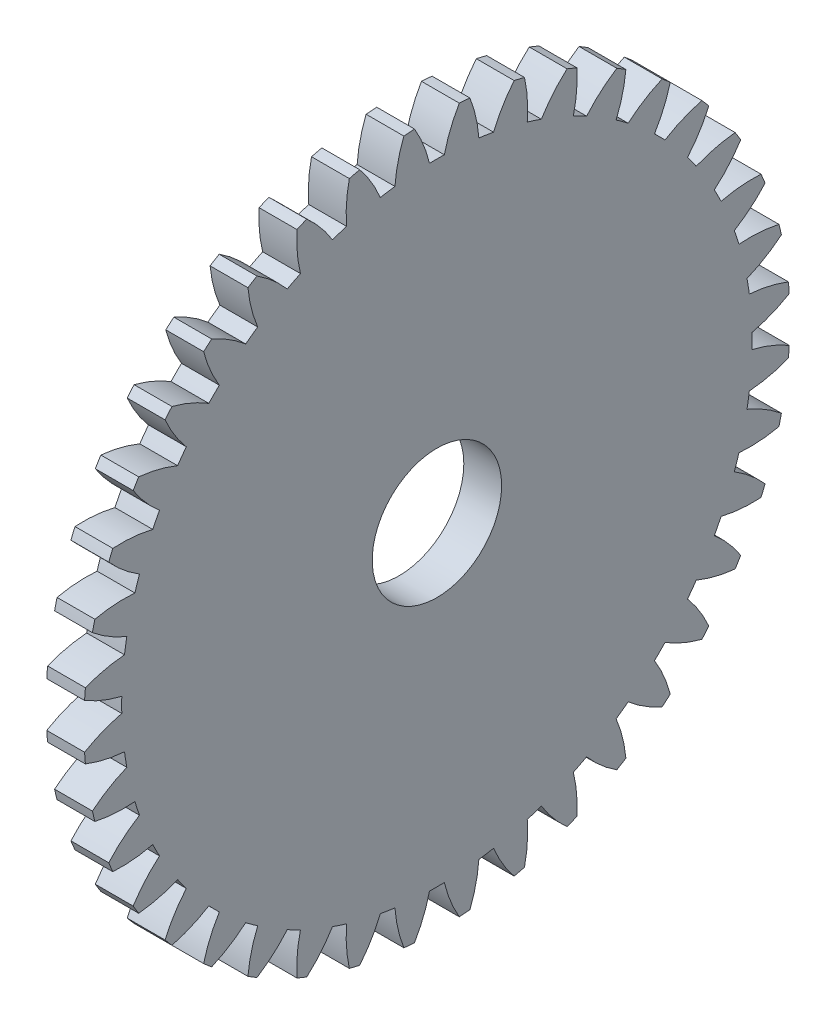
SolidWorks part; units mm, degrees
ref_plane "Plane1" through (0, 0, 0) normal (0, 0, 1) x (1, 0, 0)
ref_plane "Plane2" through (0, 0, 0) normal (0, 1, 0) x (1, 0, 0)
ref_plane "Plane3" through (0, 0, 0) normal (1, 0, 0) x (0, 0, -1)
other "Configuration Table"
sketch "HoldingSke" plane through (0, 0, 0) normal (0, 1, 0) x (1, 0, 0)
  line L0 (0, 0) -> (0.383, -0.3214)
  line L1 (-15, 0) -> (100, 0) construction
  line L2 (0, 0) -> (-2.1039, 2.3779)
  line L3 (0, 0) -> (-11.863, 4.5341)
  line L4 (0, 0) -> (6.6156, 5.5511)
  line L5 (0, 0) -> (-46.8476, -17.4728)
  line L6 (0, 0) -> (-3.7303, -2.5169)
  line L7 (-2.1039, 2.3779) -> (8.6586, 51.2059)
  line L8 (-76.2, 54.61) -> (-74.4, 54.61)
  line L9 (-71.009, 38.7566) -> (-53.1078, 45.2721)
  line L10 (-76.2, 71.12) -> (104.1128, 71.12)
  line L11 (0, 0) -> (-4.5, 0)
  line L12 (-76.2, 101.6) -> (-76.133, 101.6)
  line L13 (24.9733, 27.94) -> (52.9518, 28.4284)
  line L14 (24.9733, 27.94) -> (24.9743, 27.94)
  line L15 (24.9733, 27.94) -> (100.4006, 29.5858)
  line L16 (-63.627, -2) -> (-12.827, -2)
  circle A0 centre (0, 0) radius 5
  circle A1 centre (0, 0) radius 37.499
  circle A2 centre (0, 0) radius 37.5
  circle A3 centre (0, 0) radius 5
  dimension "MHD" = 74.998
  dimension "Hub_dia" = 75
  dimension "Bore" = 10
  dimension "MBD" = 10
  dimension "Num_teeth" = 40
  dimension "Pitch" = 0.5
  dimension "Overall_len" = 50
  dimension "Show_teeth" = 40
  dimension "Thickness" = 4.5
  dimension "OAL" = 50.0001
  dimension "T_dim" = 1.8
  dimension "Ap" = 20
  dimension "H" = 19.05
  dimension "Pitch_radius" = 180.3128
  dimension "Width" = 4.5
  dimension "Backlash" = 0.067
  dimension "Addendum_fac" = 1
  dimension "Dedendum_fac" = 1.25
  dimension "Clearance_fac" = 0.25
  dimension "Dedendum_add" = 0.001
  dimension "Module" = 2
sketch "BasProSke" plane through (0, 0, 0) normal (0, 1, 0) x (1, 0, 0)
  line L0 (-10, 0) -> (60, 0) construction
  line L1 (0, 0) -> (0, 42)
  line L2 (0, 0) -> (4.5, 0)
  line L3 (4.5, 0) -> (4.5, 42)
  line L4 (4.5, 42) -> (0, 42)
  dimension "Thickness" = 4.5
  dimension "Diameter" = 84
revolve "Base-Revolve" add sketch "BasProSke" angle 360 about L0
sketch "TooCutSke" plane through (0, 0, 0) normal (1, 0, 0) x (0, 0, -1)
  line L1 (0, 0) -> (0, 107) construction
  line L2 (0, 0) -> (-1.6876, 39.9644) construction
  line L3 (0, 0) -> (-6.2726, 79.7007) construction
  line L4 (-1.6876, 39.9644) -> (-3.1363, 39.8504) construction
  arc A0 (0.8828, 37.4886) -> (-0.8828, 37.4886) centre (0, 0) ccw
  arc A1 (2.6784, 41.94) -> (-2.6784, 41.94) centre (0, 0) ccw
  circle A2 centre (0, 0) radius 40 construction
  circle A3 centre (0, 0) radius 37.5877 construction
  arc A4 (-0.8828, 37.4886) -> (-2.6784, 41.94) centre (-16.451, 33.7965) ccw
  arc A5 (2.6784, 41.94) -> (0.8828, 37.4886) centre (16.451, 33.7965) ccw
  dimension "Root_dia" = 74.998
  dimension "Overcut_dia" = 84.0508
  dimension "Pitch_dia" = 80
  dimension "Base_dia" = 75.1754
  dimension "Flank_rad" = 16
  dimension "Half_ang" = 4.5
  dimension "Half_CT" = 1.4531
extrude "ToothCut" cut sketch "TooCutSke" along normal through all
fillet "Breaks" [suppressed] radius 0.04
fillet "RootFillets" [suppressed] radius 0.501
pattern_circular "TeethCuts" count 40 every 9 about axis through (-10, 0, 0) along (1, 0, 0) of "ToothCut", "RootFillets", "Breaks"
sketch "HubNeaOneSke" plane through (0, 0, 0) normal (-1, 0, 0) x (0, 0, 1)
  circle A0 centre (0, 0) radius 37.499
  dimension "Diameter" = 74.998
extrude "HubNearOne" [suppressed] add sketch "HubNeaOneSke" along normal blind 45.5001
sketch "HubNeaBotSke" plane through (0, 0, 0) normal (-1, 0, 0) x (0, 0, 1)
  circle A0 centre (0, 0) radius 37.499
  dimension "Diameter" = 74.998
extrude "HubNearBoth" [suppressed] add sketch "HubNeaBotSke" along normal blind 22.75
ref_plane "FarPln" through (4.5, 0, 0) normal (1, 0, 0) x (0, 0, -1)
sketch "HubFarSke" plane through (4.5, 0, 0) normal (1, 0, 0) x (0, 0, -1)
  circle A0 centre (0, 0) radius 37.499
  dimension "Diameter" = 74.998
extrude "HubFar" [suppressed] add sketch "HubFarSke" along normal blind 22.75
sketch "BorSke" plane through (0, 0, 0) normal (1, 0, 0) x (0, 0, -1)
  circle A0 centre (0, 0) radius 5
  dimension "Diameter" = 10
extrude "Bore" cut sketch "BorSke" along normal mid plane 100.0001
sketch "KeySke" plane through (0, 0, 0) normal (1, 0, 0) x (0, 0, -1)
  line L0 (-2, 0) -> (-2, 6.8)
  line L1 (-2, 6.8) -> (2, 6.8)
  line L2 (2, 6.8) -> (2, 0)
  line L3 (0, 0) -> (0, 34) construction
  line L4 (-2, 0) -> (2, 0)
  dimension "Offset" = 6.8
  dimension "Width" = 4
extrude "Keyway" [suppressed] cut sketch "KeySke" along normal mid plane 100.0001
pattern_circular "Keyway2" [suppressed] count 2 every 90 about axis through (-10, 0, 0) along (1, 0, 0)
sketch "Sketch1" plane through (4.5, 0, 0) normal (1, 0, 0) x (0, 0, -1)
  circle A0 centre (0, 0) radius 7.7
  arc A160 (-41.9154, 2.664) -> (-37.4886, 0.8828) centre (-33.7965, 16.451) ccw
  arc A161 (-37.4886, 0.8828) -> (-37.4886, -0.8828) centre (0, 0) ccw
  arc A162 (-37.4886, -0.8828) -> (-41.9154, -2.664) centre (-33.7965, -16.451) ccw
  arc A163 (-41.9154, -2.664) -> (-41.8161, -3.9259) centre (0, 0) ccw
  arc A164 (-41.8161, -3.9259) -> (-37.1652, -4.9926) centre (-35.9539, 10.9615) ccw
  arc A165 (-37.1652, -4.9926) -> (-36.889, -6.7365) centre (0, 0) ccw
  arc A166 (-36.889, -6.7365) -> (-40.9826, -9.1882) centre (-30.8069, -21.5354) ccw
  arc A167 (-40.9826, -9.1882) -> (-40.6872, -10.419) centre (0, 0) ccw
  arc A168 (-40.6872, -10.419) -> (-35.9266, -10.745) centre (-37.226, 5.2021) ccw
  arc A169 (-35.9266, -10.745) -> (-35.381, -12.4242) centre (0, 0) ccw
  arc A170 (-35.381, -12.4242) -> (-39.0407, -15.4862) centre (-27.0587, -26.0895) ccw
  arc A171 (-39.0407, -15.4862) -> (-38.5563, -16.6556) centre (0, 0) ccw
  arc A172 (-38.5563, -16.6556) -> (-33.8034, -16.2329) centre (-37.5815, -0.6853) ccw
  arc A173 (-33.8034, -16.2329) -> (-33.0018, -17.8061) centre (0, 0) ccw
  arc A174 (-33.0018, -17.8061) -> (-36.1375, -21.4028) centre (-22.6443, -30.0012) ccw
  arc A175 (-36.1375, -21.4028) -> (-35.4761, -22.4821) centre (0, 0) ccw
  arc A176 (-35.4761, -22.4821) -> (-30.8478, -21.321) centre (-37.0116, -6.5559) ccw
  arc A177 (-30.8478, -21.321) -> (-29.81, -22.7495) centre (0, 0) ccw
  arc A178 (-29.81, -22.7495) -> (-32.3445, -26.7925) centre (-17.6723, -33.1742) ccw
  arc A179 (-32.3445, -26.7925) -> (-31.5224, -27.755) centre (0, 0) ccw
  arc A180 (-31.5224, -27.755) -> (-27.1327, -25.8842) centre (-35.5303, -12.2651) ccw
  arc A181 (-27.1327, -25.8842) -> (-25.8842, -27.1327) centre (0, 0) ccw
  arc A182 (-25.8842, -27.1327) -> (-27.755, -31.5224) centre (-12.2651, -35.5303) ccw
  arc A183 (-27.755, -31.5224) -> (-26.7925, -32.3445) centre (0, 0) ccw
  arc A184 (-26.7925, -32.3445) -> (-22.7495, -29.81) centre (-33.1742, -17.6723) ccw
  arc A185 (-22.7495, -29.81) -> (-21.321, -30.8478) centre (0, 0) ccw
  arc A186 (-21.321, -30.8478) -> (-22.4821, -35.4761) centre (-6.5559, -37.0116) ccw
  arc A187 (-22.4821, -35.4761) -> (-21.4028, -36.1375) centre (0, 0) ccw
  arc A188 (-21.4028, -36.1375) -> (-17.8061, -33.0018) centre (-30.0012, -22.6443) ccw
  arc A189 (-17.8061, -33.0018) -> (-16.2329, -33.8034) centre (0, 0) ccw
  arc A190 (-16.2329, -33.8034) -> (-16.6556, -38.5563) centre (-0.6853, -37.5815) ccw
  arc A191 (-16.6556, -38.5563) -> (-15.4862, -39.0407) centre (0, 0) ccw
  arc A192 (-15.4862, -39.0407) -> (-12.4242, -35.381) centre (-26.0895, -27.0587) ccw
  arc A193 (-12.4242, -35.381) -> (-10.745, -35.9266) centre (0, 0) ccw
  arc A194 (-10.745, -35.9266) -> (-10.419, -40.6872) centre (5.2021, -37.226) ccw
  arc A195 (-10.419, -40.6872) -> (-9.1882, -40.9826) centre (0, 0) ccw
  arc A196 (-9.1882, -40.9826) -> (-6.7365, -36.889) centre (-21.5354, -30.8069) ccw
  arc A197 (-6.7365, -36.889) -> (-4.9926, -37.1652) centre (0, 0) ccw
  arc A198 (-4.9926, -37.1652) -> (-3.9259, -41.8161) centre (10.9615, -35.9539) ccw
  arc A199 (-3.9259, -41.8161) -> (-2.664, -41.9154) centre (0, 0) ccw
  arc A200 (-2.664, -41.9154) -> (-0.8828, -37.4886) centre (-16.451, -33.7965) ccw
  arc A201 (-0.8828, -37.4886) -> (0.8828, -37.4886) centre (0, 0) ccw
  arc A202 (0.8828, -37.4886) -> (2.664, -41.9154) centre (16.451, -33.7965) ccw
  arc A203 (2.664, -41.9154) -> (3.9259, -41.8161) centre (0, 0) ccw
  arc A204 (3.9259, -41.8161) -> (4.9926, -37.1652) centre (-10.9615, -35.9539) ccw
  arc A205 (4.9926, -37.1652) -> (6.7365, -36.889) centre (0, 0) ccw
  arc A206 (6.7365, -36.889) -> (9.1882, -40.9826) centre (21.5354, -30.8069) ccw
  arc A207 (9.1882, -40.9826) -> (10.419, -40.6872) centre (0, 0) ccw
  arc A208 (10.419, -40.6872) -> (10.745, -35.9266) centre (-5.2021, -37.226) ccw
  arc A209 (10.745, -35.9266) -> (12.4242, -35.381) centre (0, 0) ccw
  arc A210 (12.4242, -35.381) -> (15.4862, -39.0407) centre (26.0895, -27.0587) ccw
  arc A211 (15.4862, -39.0407) -> (16.6556, -38.5563) centre (0, 0) ccw
  arc A212 (16.6556, -38.5563) -> (16.2329, -33.8034) centre (0.6853, -37.5815) ccw
  arc A213 (16.2329, -33.8034) -> (17.8061, -33.0018) centre (0, 0) ccw
  arc A214 (17.8061, -33.0018) -> (21.4028, -36.1375) centre (30.0012, -22.6443) ccw
  arc A215 (21.4028, -36.1375) -> (22.4821, -35.4761) centre (0, 0) ccw
  arc A216 (22.4821, -35.4761) -> (21.321, -30.8478) centre (6.5559, -37.0116) ccw
  arc A217 (21.321, -30.8478) -> (22.7495, -29.81) centre (0, 0) ccw
  arc A218 (22.7495, -29.81) -> (26.7925, -32.3445) centre (33.1742, -17.6723) ccw
  arc A219 (26.7925, -32.3445) -> (27.755, -31.5224) centre (0, 0) ccw
  arc A220 (27.755, -31.5224) -> (25.8842, -27.1327) centre (12.2651, -35.5303) ccw
  arc A221 (25.8842, -27.1327) -> (27.1327, -25.8842) centre (0, 0) ccw
  arc A222 (27.1327, -25.8842) -> (31.5224, -27.755) centre (35.5303, -12.2651) ccw
  arc A223 (31.5224, -27.755) -> (32.3445, -26.7925) centre (0, 0) ccw
  arc A224 (32.3445, -26.7925) -> (29.81, -22.7495) centre (17.6723, -33.1742) ccw
  arc A225 (29.81, -22.7495) -> (30.8478, -21.321) centre (0, 0) ccw
  arc A226 (30.8478, -21.321) -> (35.4761, -22.4821) centre (37.0116, -6.5559) ccw
  arc A227 (35.4761, -22.4821) -> (36.1375, -21.4028) centre (0, 0) ccw
  arc A228 (36.1375, -21.4028) -> (33.0018, -17.8061) centre (22.6443, -30.0012) ccw
  arc A229 (33.0018, -17.8061) -> (33.8034, -16.2329) centre (0, 0) ccw
  arc A230 (33.8034, -16.2329) -> (38.5563, -16.6556) centre (37.5815, -0.6853) ccw
  arc A231 (38.5563, -16.6556) -> (39.0407, -15.4862) centre (0, 0) ccw
  arc A232 (39.0407, -15.4862) -> (35.381, -12.4242) centre (27.0587, -26.0895) ccw
  arc A233 (35.381, -12.4242) -> (35.9266, -10.745) centre (0, 0) ccw
  arc A234 (35.9266, -10.745) -> (40.6872, -10.419) centre (37.226, 5.2021) ccw
  arc A235 (40.6872, -10.419) -> (40.9826, -9.1882) centre (0, 0) ccw
  arc A236 (40.9826, -9.1882) -> (36.889, -6.7365) centre (30.8069, -21.5354) ccw
  arc A237 (36.889, -6.7365) -> (37.1652, -4.9926) centre (0, 0) ccw
  arc A238 (37.1652, -4.9926) -> (41.8161, -3.9259) centre (35.9539, 10.9615) ccw
  arc A239 (41.8161, -3.9259) -> (41.9154, -2.664) centre (0, 0) ccw
  arc A240 (41.9154, -2.664) -> (37.4886, -0.8828) centre (33.7965, -16.451) ccw
  arc A241 (37.4886, -0.8828) -> (37.4886, 0.8828) centre (0, 0) ccw
  arc A242 (37.4886, 0.8828) -> (41.9154, 2.664) centre (33.7965, 16.451) ccw
  arc A243 (41.9154, 2.664) -> (41.8161, 3.9259) centre (0, 0) ccw
  arc A244 (41.8161, 3.9259) -> (37.1652, 4.9926) centre (35.9539, -10.9615) ccw
  arc A245 (37.1652, 4.9926) -> (36.889, 6.7365) centre (0, 0) ccw
  arc A246 (36.889, 6.7365) -> (40.9826, 9.1882) centre (30.8069, 21.5354) ccw
  arc A247 (40.9826, 9.1882) -> (40.6872, 10.419) centre (0, 0) ccw
  arc A248 (40.6872, 10.419) -> (35.9266, 10.745) centre (37.226, -5.2021) ccw
  arc A249 (35.9266, 10.745) -> (35.381, 12.4242) centre (0, 0) ccw
  arc A250 (35.381, 12.4242) -> (39.0407, 15.4862) centre (27.0587, 26.0895) ccw
  arc A251 (39.0407, 15.4862) -> (38.5563, 16.6556) centre (0, 0) ccw
  arc A252 (38.5563, 16.6556) -> (33.8034, 16.2329) centre (37.5815, 0.6853) ccw
  arc A253 (33.8034, 16.2329) -> (33.0018, 17.8061) centre (0, 0) ccw
  arc A254 (33.0018, 17.8061) -> (36.1375, 21.4028) centre (22.6443, 30.0012) ccw
  arc A255 (36.1375, 21.4028) -> (35.4761, 22.4821) centre (0, 0) ccw
  arc A256 (35.4761, 22.4821) -> (30.8478, 21.321) centre (37.0116, 6.5559) ccw
  arc A257 (30.8478, 21.321) -> (29.81, 22.7495) centre (0, 0) ccw
  arc A258 (29.81, 22.7495) -> (32.3445, 26.7925) centre (17.6723, 33.1742) ccw
  arc A259 (32.3445, 26.7925) -> (31.5224, 27.755) centre (0, 0) ccw
  arc A260 (31.5224, 27.755) -> (27.1327, 25.8842) centre (35.5303, 12.2651) ccw
  arc A261 (27.1327, 25.8842) -> (25.8842, 27.1327) centre (0, 0) ccw
  arc A262 (25.8842, 27.1327) -> (27.755, 31.5224) centre (12.2651, 35.5303) ccw
  arc A263 (27.755, 31.5224) -> (26.7925, 32.3445) centre (0, 0) ccw
  arc A264 (26.7925, 32.3445) -> (22.7495, 29.81) centre (33.1742, 17.6723) ccw
  arc A265 (22.7495, 29.81) -> (21.321, 30.8478) centre (0, 0) ccw
  arc A266 (21.321, 30.8478) -> (22.4821, 35.4761) centre (6.5559, 37.0116) ccw
  arc A267 (22.4821, 35.4761) -> (21.4028, 36.1375) centre (0, 0) ccw
  arc A268 (21.4028, 36.1375) -> (17.8061, 33.0018) centre (30.0012, 22.6443) ccw
  arc A269 (17.8061, 33.0018) -> (16.2329, 33.8034) centre (0, 0) ccw
  arc A270 (16.2329, 33.8034) -> (16.6556, 38.5563) centre (0.6853, 37.5815) ccw
  arc A271 (16.6556, 38.5563) -> (15.4862, 39.0407) centre (0, 0) ccw
  arc A272 (15.4862, 39.0407) -> (12.4242, 35.381) centre (26.0895, 27.0587) ccw
  arc A273 (12.4242, 35.381) -> (10.745, 35.9266) centre (0, 0) ccw
  arc A274 (10.745, 35.9266) -> (10.419, 40.6872) centre (-5.2021, 37.226) ccw
  arc A275 (10.419, 40.6872) -> (9.1882, 40.9826) centre (0, 0) ccw
  arc A276 (9.1882, 40.9826) -> (6.7365, 36.889) centre (21.5354, 30.8069) ccw
  arc A277 (6.7365, 36.889) -> (4.9926, 37.1652) centre (0, 0) ccw
  arc A278 (4.9926, 37.1652) -> (3.9259, 41.8161) centre (-10.9615, 35.9539) ccw
  arc A279 (3.9259, 41.8161) -> (2.664, 41.9154) centre (0, 0) ccw
  arc A280 (2.664, 41.9154) -> (0.8828, 37.4886) centre (16.451, 33.7965) ccw
  arc A281 (0.8828, 37.4886) -> (-0.8828, 37.4886) centre (0, 0) ccw
  arc A282 (-0.8828, 37.4886) -> (-2.664, 41.9154) centre (-16.451, 33.7965) ccw
  arc A283 (-2.664, 41.9154) -> (-3.9259, 41.8161) centre (0, 0) ccw
  arc A284 (-3.9259, 41.8161) -> (-4.9926, 37.1652) centre (10.9615, 35.9539) ccw
  arc A285 (-4.9926, 37.1652) -> (-6.7365, 36.889) centre (0, 0) ccw
  arc A286 (-6.7365, 36.889) -> (-9.1882, 40.9826) centre (-21.5354, 30.8069) ccw
  arc A287 (-9.1882, 40.9826) -> (-10.419, 40.6872) centre (0, 0) ccw
  arc A288 (-10.419, 40.6872) -> (-10.745, 35.9266) centre (5.2021, 37.226) ccw
  arc A289 (-10.745, 35.9266) -> (-12.4242, 35.381) centre (0, 0) ccw
  arc A290 (-12.4242, 35.381) -> (-15.4862, 39.0407) centre (-26.0895, 27.0587) ccw
  arc A291 (-15.4862, 39.0407) -> (-16.6556, 38.5563) centre (0, 0) ccw
  arc A292 (-16.6556, 38.5563) -> (-16.2329, 33.8034) centre (-0.6853, 37.5815) ccw
  arc A293 (-16.2329, 33.8034) -> (-17.8061, 33.0018) centre (0, 0) ccw
  arc A294 (-17.8061, 33.0018) -> (-21.4028, 36.1375) centre (-30.0012, 22.6443) ccw
  arc A295 (-21.4028, 36.1375) -> (-22.4821, 35.4761) centre (0, 0) ccw
  arc A296 (-22.4821, 35.4761) -> (-21.321, 30.8478) centre (-6.5559, 37.0116) ccw
  arc A297 (-21.321, 30.8478) -> (-22.7495, 29.81) centre (0, 0) ccw
  arc A298 (-22.7495, 29.81) -> (-26.7925, 32.3445) centre (-33.1742, 17.6723) ccw
  arc A299 (-26.7925, 32.3445) -> (-27.755, 31.5224) centre (0, 0) ccw
  arc A300 (-27.755, 31.5224) -> (-25.8842, 27.1327) centre (-12.2651, 35.5303) ccw
  arc A301 (-25.8842, 27.1327) -> (-27.1327, 25.8842) centre (0, 0) ccw
  arc A302 (-27.1327, 25.8842) -> (-31.5224, 27.755) centre (-35.5303, 12.2651) ccw
  arc A303 (-31.5224, 27.755) -> (-32.3445, 26.7925) centre (0, 0) ccw
  arc A304 (-32.3445, 26.7925) -> (-29.81, 22.7495) centre (-17.6723, 33.1742) ccw
  arc A305 (-29.81, 22.7495) -> (-30.8478, 21.321) centre (0, 0) ccw
  arc A306 (-30.8478, 21.321) -> (-35.4761, 22.4821) centre (-37.0116, 6.5559) ccw
  arc A307 (-35.4761, 22.4821) -> (-36.1375, 21.4028) centre (0, 0) ccw
  arc A308 (-36.1375, 21.4028) -> (-33.0018, 17.8061) centre (-22.6443, 30.0012) ccw
  arc A309 (-33.0018, 17.8061) -> (-33.8034, 16.2329) centre (0, 0) ccw
  arc A310 (-33.8034, 16.2329) -> (-38.5563, 16.6556) centre (-37.5815, 0.6853) ccw
  arc A311 (-38.5563, 16.6556) -> (-39.0407, 15.4862) centre (0, 0) ccw
  arc A312 (-39.0407, 15.4862) -> (-35.381, 12.4242) centre (-27.0587, 26.0895) ccw
  arc A313 (-35.381, 12.4242) -> (-35.9266, 10.745) centre (0, 0) ccw
  arc A314 (-35.9266, 10.745) -> (-40.6872, 10.419) centre (-37.226, -5.2021) ccw
  arc A315 (-40.6872, 10.419) -> (-40.9826, 9.1882) centre (0, 0) ccw
  arc A316 (-40.9826, 9.1882) -> (-36.889, 6.7365) centre (-30.8069, 21.5354) ccw
  arc A317 (-36.889, 6.7365) -> (-37.1652, 4.9926) centre (0, 0) ccw
  arc A318 (-37.1652, 4.9926) -> (-41.8161, 3.9259) centre (-35.9539, -10.9615) ccw
  arc A319 (-41.8161, 3.9259) -> (-41.9154, 2.664) centre (0, 0) ccw
  arc A320 (-41.9154, 2.664) -> (-37.4886, 0.8828) centre (-33.7965, 16.451) ccw
  arc A321 (-37.4886, 0.8828) -> (-37.4886, -0.8828) centre (0, 0) ccw
  arc A322 (-37.4886, -0.8828) -> (-41.9154, -2.664) centre (-33.7965, -16.451) ccw
  arc A323 (-41.9154, -2.664) -> (-41.8161, -3.9259) centre (0, 0) ccw
  arc A324 (-41.8161, -3.9259) -> (-37.1652, -4.9926) centre (-35.9539, 10.9615) ccw
  arc A325 (-37.1652, -4.9926) -> (-36.889, -6.7365) centre (0, 0) ccw
  arc A326 (-36.889, -6.7365) -> (-40.9826, -9.1882) centre (-30.8069, -21.5354) ccw
  arc A327 (-40.9826, -9.1882) -> (-40.6872, -10.419) centre (0, 0) ccw
  arc A328 (-40.6872, -10.419) -> (-35.9266, -10.745) centre (-37.226, 5.2021) ccw
  arc A329 (-35.9266, -10.745) -> (-35.381, -12.4242) centre (0, 0) ccw
  arc A330 (-35.381, -12.4242) -> (-39.0407, -15.4862) centre (-27.0587, -26.0895) ccw
  arc A331 (-39.0407, -15.4862) -> (-38.5563, -16.6556) centre (0, 0) ccw
  arc A332 (-38.5563, -16.6556) -> (-33.8034, -16.2329) centre (-37.5815, -0.6853) ccw
  arc A333 (-33.8034, -16.2329) -> (-33.0018, -17.8061) centre (0, 0) ccw
  arc A334 (-33.0018, -17.8061) -> (-36.1375, -21.4028) centre (-22.6443, -30.0012) ccw
  arc A335 (-36.1375, -21.4028) -> (-35.4761, -22.4821) centre (0, 0) ccw
  arc A336 (-35.4761, -22.4821) -> (-30.8478, -21.321) centre (-37.0116, -6.5559) ccw
  arc A337 (-30.8478, -21.321) -> (-29.81, -22.7495) centre (0, 0) ccw
  arc A338 (-29.81, -22.7495) -> (-32.3445, -26.7925) centre (-17.6723, -33.1742) ccw
  arc A339 (-32.3445, -26.7925) -> (-31.5224, -27.755) centre (0, 0) ccw
  arc A340 (-31.5224, -27.755) -> (-27.1327, -25.8842) centre (-35.5303, -12.2651) ccw
  arc A341 (-27.1327, -25.8842) -> (-25.8842, -27.1327) centre (0, 0) ccw
  arc A342 (-25.8842, -27.1327) -> (-27.755, -31.5224) centre (-12.2651, -35.5303) ccw
  arc A343 (-27.755, -31.5224) -> (-26.7925, -32.3445) centre (0, 0) ccw
  arc A344 (-26.7925, -32.3445) -> (-22.7495, -29.81) centre (-33.1742, -17.6723) ccw
  arc A345 (-22.7495, -29.81) -> (-21.321, -30.8478) centre (0, 0) ccw
  arc A346 (-21.321, -30.8478) -> (-22.4821, -35.4761) centre (-6.5559, -37.0116) ccw
  arc A347 (-22.4821, -35.4761) -> (-21.4028, -36.1375) centre (0, 0) ccw
  arc A348 (-21.4028, -36.1375) -> (-17.8061, -33.0018) centre (-30.0012, -22.6443) ccw
  arc A349 (-17.8061, -33.0018) -> (-16.2329, -33.8034) centre (0, 0) ccw
  arc A350 (-16.2329, -33.8034) -> (-16.6556, -38.5563) centre (-0.6853, -37.5815) ccw
  arc A351 (-16.6556, -38.5563) -> (-15.4862, -39.0407) centre (0, 0) ccw
  arc A352 (-15.4862, -39.0407) -> (-12.4242, -35.381) centre (-26.0895, -27.0587) ccw
  arc A353 (-12.4242, -35.381) -> (-10.745, -35.9266) centre (0, 0) ccw
  arc A354 (-10.745, -35.9266) -> (-10.419, -40.6872) centre (5.2021, -37.226) ccw
  arc A355 (-10.419, -40.6872) -> (-9.1882, -40.9826) centre (0, 0) ccw
  arc A356 (-9.1882, -40.9826) -> (-6.7365, -36.889) centre (-21.5354, -30.8069) ccw
  arc A357 (-6.7365, -36.889) -> (-4.9926, -37.1652) centre (0, 0) ccw
  arc A358 (-4.9926, -37.1652) -> (-3.9259, -41.8161) centre (10.9615, -35.9539) ccw
  arc A359 (-3.9259, -41.8161) -> (-2.664, -41.9154) centre (0, 0) ccw
  arc A360 (-2.664, -41.9154) -> (-0.8828, -37.4886) centre (-16.451, -33.7965) ccw
  arc A361 (-0.8828, -37.4886) -> (0.8828, -37.4886) centre (0, 0) ccw
  arc A362 (0.8828, -37.4886) -> (2.664, -41.9154) centre (16.451, -33.7965) ccw
  arc A363 (2.664, -41.9154) -> (3.9259, -41.8161) centre (0, 0) ccw
  arc A364 (3.9259, -41.8161) -> (4.9926, -37.1652) centre (-10.9615, -35.9539) ccw
  arc A365 (4.9926, -37.1652) -> (6.7365, -36.889) centre (0, 0) ccw
  arc A366 (6.7365, -36.889) -> (9.1882, -40.9826) centre (21.5354, -30.8069) ccw
  arc A367 (9.1882, -40.9826) -> (10.419, -40.6872) centre (0, 0) ccw
  arc A368 (10.419, -40.6872) -> (10.745, -35.9266) centre (-5.2021, -37.226) ccw
  arc A369 (10.745, -35.9266) -> (12.4242, -35.381) centre (0, 0) ccw
  arc A370 (12.4242, -35.381) -> (15.4862, -39.0407) centre (26.0895, -27.0587) ccw
  arc A371 (15.4862, -39.0407) -> (16.6556, -38.5563) centre (0, 0) ccw
  arc A372 (16.6556, -38.5563) -> (16.2329, -33.8034) centre (0.6853, -37.5815) ccw
  arc A373 (16.2329, -33.8034) -> (17.8061, -33.0018) centre (0, 0) ccw
  arc A374 (17.8061, -33.0018) -> (21.4028, -36.1375) centre (30.0012, -22.6443) ccw
  arc A375 (21.4028, -36.1375) -> (22.4821, -35.4761) centre (0, 0) ccw
  arc A376 (22.4821, -35.4761) -> (21.321, -30.8478) centre (6.5559, -37.0116) ccw
  arc A377 (21.321, -30.8478) -> (22.7495, -29.81) centre (0, 0) ccw
  arc A378 (22.7495, -29.81) -> (26.7925, -32.3445) centre (33.1742, -17.6723) ccw
  arc A379 (26.7925, -32.3445) -> (27.755, -31.5224) centre (0, 0) ccw
  arc A380 (27.755, -31.5224) -> (25.8842, -27.1327) centre (12.2651, -35.5303) ccw
  arc A381 (25.8842, -27.1327) -> (27.1327, -25.8842) centre (0, 0) ccw
  arc A382 (27.1327, -25.8842) -> (31.5224, -27.755) centre (35.5303, -12.2651) ccw
  arc A383 (31.5224, -27.755) -> (32.3445, -26.7925) centre (0, 0) ccw
  arc A384 (32.3445, -26.7925) -> (29.81, -22.7495) centre (17.6723, -33.1742) ccw
  arc A385 (29.81, -22.7495) -> (30.8478, -21.321) centre (0, 0) ccw
  arc A386 (30.8478, -21.321) -> (35.4761, -22.4821) centre (37.0116, -6.5559) ccw
  arc A387 (35.4761, -22.4821) -> (36.1375, -21.4028) centre (0, 0) ccw
  arc A388 (36.1375, -21.4028) -> (33.0018, -17.8061) centre (22.6443, -30.0012) ccw
  arc A389 (33.0018, -17.8061) -> (33.8034, -16.2329) centre (0, 0) ccw
  arc A390 (33.8034, -16.2329) -> (38.5563, -16.6556) centre (37.5815, -0.6853) ccw
  arc A391 (38.5563, -16.6556) -> (39.0407, -15.4862) centre (0, 0) ccw
  arc A392 (39.0407, -15.4862) -> (35.381, -12.4242) centre (27.0587, -26.0895) ccw
  arc A393 (35.381, -12.4242) -> (35.9266, -10.745) centre (0, 0) ccw
  arc A394 (35.9266, -10.745) -> (40.6872, -10.419) centre (37.226, 5.2021) ccw
  arc A395 (40.6872, -10.419) -> (40.9826, -9.1882) centre (0, 0) ccw
  arc A396 (40.9826, -9.1882) -> (36.889, -6.7365) centre (30.8069, -21.5354) ccw
  arc A397 (36.889, -6.7365) -> (37.1652, -4.9926) centre (0, 0) ccw
  arc A398 (37.1652, -4.9926) -> (41.8161, -3.9259) centre (35.9539, 10.9615) ccw
  arc A399 (41.8161, -3.9259) -> (41.9154, -2.664) centre (0, 0) ccw
  arc A400 (41.9154, -2.664) -> (37.4886, -0.8828) centre (33.7965, -16.451) ccw
  arc A401 (37.4886, -0.8828) -> (37.4886, 0.8828) centre (0, 0) ccw
  arc A402 (37.4886, 0.8828) -> (41.9154, 2.664) centre (33.7965, 16.451) ccw
  arc A403 (41.9154, 2.664) -> (41.8161, 3.9259) centre (0, 0) ccw
  arc A404 (41.8161, 3.9259) -> (37.1652, 4.9926) centre (35.9539, -10.9615) ccw
  arc A405 (37.1652, 4.9926) -> (36.889, 6.7365) centre (0, 0) ccw
  arc A406 (36.889, 6.7365) -> (40.9826, 9.1882) centre (30.8069, 21.5354) ccw
  arc A407 (40.9826, 9.1882) -> (40.6872, 10.419) centre (0, 0) ccw
  arc A408 (40.6872, 10.419) -> (35.9266, 10.745) centre (37.226, -5.2021) ccw
  arc A409 (35.9266, 10.745) -> (35.381, 12.4242) centre (0, 0) ccw
  arc A410 (35.381, 12.4242) -> (39.0407, 15.4862) centre (27.0587, 26.0895) ccw
  arc A411 (39.0407, 15.4862) -> (38.5563, 16.6556) centre (0, 0) ccw
  arc A412 (38.5563, 16.6556) -> (33.8034, 16.2329) centre (37.5815, 0.6853) ccw
  arc A413 (33.8034, 16.2329) -> (33.0018, 17.8061) centre (0, 0) ccw
  arc A414 (33.0018, 17.8061) -> (36.1375, 21.4028) centre (22.6443, 30.0012) ccw
  arc A415 (36.1375, 21.4028) -> (35.4761, 22.4821) centre (0, 0) ccw
  arc A416 (35.4761, 22.4821) -> (30.8478, 21.321) centre (37.0116, 6.5559) ccw
  arc A417 (30.8478, 21.321) -> (29.81, 22.7495) centre (0, 0) ccw
  arc A418 (29.81, 22.7495) -> (32.3445, 26.7925) centre (17.6723, 33.1742) ccw
  arc A419 (32.3445, 26.7925) -> (31.5224, 27.755) centre (0, 0) ccw
  arc A420 (31.5224, 27.755) -> (27.1327, 25.8842) centre (35.5303, 12.2651) ccw
  arc A421 (27.1327, 25.8842) -> (25.8842, 27.1327) centre (0, 0) ccw
  arc A422 (25.8842, 27.1327) -> (27.755, 31.5224) centre (12.2651, 35.5303) ccw
  arc A423 (27.755, 31.5224) -> (26.7925, 32.3445) centre (0, 0) ccw
  arc A424 (26.7925, 32.3445) -> (22.7495, 29.81) centre (33.1742, 17.6723) ccw
  arc A425 (22.7495, 29.81) -> (21.321, 30.8478) centre (0, 0) ccw
  arc A426 (21.321, 30.8478) -> (22.4821, 35.4761) centre (6.5559, 37.0116) ccw
  arc A427 (22.4821, 35.4761) -> (21.4028, 36.1375) centre (0, 0) ccw
  arc A428 (21.4028, 36.1375) -> (17.8061, 33.0018) centre (30.0012, 22.6443) ccw
  arc A429 (17.8061, 33.0018) -> (16.2329, 33.8034) centre (0, 0) ccw
  arc A430 (16.2329, 33.8034) -> (16.6556, 38.5563) centre (0.6853, 37.5815) ccw
  arc A431 (16.6556, 38.5563) -> (15.4862, 39.0407) centre (0, 0) ccw
  arc A432 (15.4862, 39.0407) -> (12.4242, 35.381) centre (26.0895, 27.0587) ccw
  arc A433 (12.4242, 35.381) -> (10.745, 35.9266) centre (0, 0) ccw
  arc A434 (10.745, 35.9266) -> (10.419, 40.6872) centre (-5.2021, 37.226) ccw
  arc A435 (10.419, 40.6872) -> (9.1882, 40.9826) centre (0, 0) ccw
  arc A436 (9.1882, 40.9826) -> (6.7365, 36.889) centre (21.5354, 30.8069) ccw
  arc A437 (6.7365, 36.889) -> (4.9926, 37.1652) centre (0, 0) ccw
  arc A438 (4.9926, 37.1652) -> (3.9259, 41.8161) centre (-10.9615, 35.9539) ccw
  arc A439 (3.9259, 41.8161) -> (2.664, 41.9154) centre (0, 0) ccw
  arc A440 (2.664, 41.9154) -> (0.8828, 37.4886) centre (16.451, 33.7965) ccw
  arc A441 (0.8828, 37.4886) -> (-0.8828, 37.4886) centre (0, 0) ccw
  arc A442 (-0.8828, 37.4886) -> (-2.664, 41.9154) centre (-16.451, 33.7965) ccw
  arc A443 (-2.664, 41.9154) -> (-3.9259, 41.8161) centre (0, 0) ccw
  arc A444 (-3.9259, 41.8161) -> (-4.9926, 37.1652) centre (10.9615, 35.9539) ccw
  arc A445 (-4.9926, 37.1652) -> (-6.7365, 36.889) centre (0, 0) ccw
  arc A446 (-6.7365, 36.889) -> (-9.1882, 40.9826) centre (-21.5354, 30.8069) ccw
  arc A447 (-9.1882, 40.9826) -> (-10.419, 40.6872) centre (0, 0) ccw
  arc A448 (-10.419, 40.6872) -> (-10.745, 35.9266) centre (5.2021, 37.226) ccw
  arc A449 (-10.745, 35.9266) -> (-12.4242, 35.381) centre (0, 0) ccw
  arc A450 (-12.4242, 35.381) -> (-15.4862, 39.0407) centre (-26.0895, 27.0587) ccw
  arc A451 (-15.4862, 39.0407) -> (-16.6556, 38.5563) centre (0, 0) ccw
  arc A452 (-16.6556, 38.5563) -> (-16.2329, 33.8034) centre (-0.6853, 37.5815) ccw
  arc A453 (-16.2329, 33.8034) -> (-17.8061, 33.0018) centre (0, 0) ccw
  arc A454 (-17.8061, 33.0018) -> (-21.4028, 36.1375) centre (-30.0012, 22.6443) ccw
  arc A455 (-21.4028, 36.1375) -> (-22.4821, 35.4761) centre (0, 0) ccw
  arc A456 (-22.4821, 35.4761) -> (-21.321, 30.8478) centre (-6.5559, 37.0116) ccw
  arc A457 (-21.321, 30.8478) -> (-22.7495, 29.81) centre (0, 0) ccw
  arc A458 (-22.7495, 29.81) -> (-26.7925, 32.3445) centre (-33.1742, 17.6723) ccw
  arc A459 (-26.7925, 32.3445) -> (-27.755, 31.5224) centre (0, 0) ccw
  arc A460 (-27.755, 31.5224) -> (-25.8842, 27.1327) centre (-12.2651, 35.5303) ccw
  arc A461 (-25.8842, 27.1327) -> (-27.1327, 25.8842) centre (0, 0) ccw
  arc A462 (-27.1327, 25.8842) -> (-31.5224, 27.755) centre (-35.5303, 12.2651) ccw
  arc A463 (-31.5224, 27.755) -> (-32.3445, 26.7925) centre (0, 0) ccw
  arc A464 (-32.3445, 26.7925) -> (-29.81, 22.7495) centre (-17.6723, 33.1742) ccw
  arc A465 (-29.81, 22.7495) -> (-30.8478, 21.321) centre (0, 0) ccw
  arc A466 (-30.8478, 21.321) -> (-35.4761, 22.4821) centre (-37.0116, 6.5559) ccw
  arc A467 (-35.4761, 22.4821) -> (-36.1375, 21.4028) centre (0, 0) ccw
  arc A468 (-36.1375, 21.4028) -> (-33.0018, 17.8061) centre (-22.6443, 30.0012) ccw
  arc A469 (-33.0018, 17.8061) -> (-33.8034, 16.2329) centre (0, 0) ccw
  arc A470 (-33.8034, 16.2329) -> (-38.5563, 16.6556) centre (-37.5815, 0.6853) ccw
  arc A471 (-38.5563, 16.6556) -> (-39.0407, 15.4862) centre (0, 0) ccw
  arc A472 (-39.0407, 15.4862) -> (-35.381, 12.4242) centre (-27.0587, 26.0895) ccw
  arc A473 (-35.381, 12.4242) -> (-35.9266, 10.745) centre (0, 0) ccw
  arc A474 (-35.9266, 10.745) -> (-40.6872, 10.419) centre (-37.226, -5.2021) ccw
  arc A475 (-40.6872, 10.419) -> (-40.9826, 9.1882) centre (0, 0) ccw
  arc A476 (-40.9826, 9.1882) -> (-36.889, 6.7365) centre (-30.8069, 21.5354) ccw
  arc A477 (-36.889, 6.7365) -> (-37.1652, 4.9926) centre (0, 0) ccw
  arc A478 (-37.1652, 4.9926) -> (-41.8161, 3.9259) centre (-35.9539, -10.9615) ccw
  arc A479 (-41.8161, 3.9259) -> (-41.9154, 2.664) centre (0, 0) ccw
  dimension "D2" = 15.4
  dimension "D1" = 0
extrude "Cut-Extrude1" cut sketch "Sketch1" against normal through all contours A0
equation "' \"Module@HoldingSke\" = 6.35"
equation "' \"Num_teeth@HoldingSke\" = 12"
equation "' \"Ap@HoldingSke\" =  20"
equation "' \"Ap@HoldingSke\" = 20"
equation "' \"Width@HoldingSke\" = 0.5 * 25.4"
equation "' \"Hub_dia@HoldingSke\"= 1 * 25.4"
equation "' \"Hub_dia@HoldingSke\" = 1 * 25.4"
equation "' \"Overall_len@HoldingSke\" = 1.0 * 25.4"
equation "' \"Bore@HoldingSke\" = 0.75 * 25.4"
equation "' \"T_dim@HoldingSke\" = 0.1 * 25.4"
equation "' \"Width@KeySke\" = 0.25 * 25.4"
equation "' \"Show_teeth@HoldingSke\" = 13"
equation "' \"Backlash@HoldingSke\" = 0.009 * 25.4"
equation "' \"Addendum_fac@HoldingSke\" = 1.0"
equation "' \"Dedendum_fac@HoldingSke\" = 1.25"
equation "' \"Dedendum_add@HoldingSke\" = 0.00005 * 25.4"
equation "' \"Clearance_fac@HoldingSke\" = 0.25"
equation "\"Pitch@HoldingSke\" = 1 / \"Module@HoldingSke\""
equation "\"Overcut_dia@TooCutSke\" = (\"Num_teeth@HoldingSke\" + 2 * \"Addendum_fac@HoldingSke\") / \"Pitch@HoldingSke\" + 0.002 * 25.4"
equation "\"Pitch_dia@TooCutSke\" = \"Num_teeth@HoldingSke\" / \"Pitch@HoldingSke\""
equation "\"Base_dia@TooCutSke\" = \"Num_teeth@HoldingSke\" / \"Pitch@HoldingSke\" * cos((\"Ap@HoldingSke\"  * 3.14159265 / 180))"
equation "\"Root_dia@TooCutSke\" = (\"Num_teeth@HoldingSke\" + 2) / \"Pitch@HoldingSke\" - 2 * (\"Addendum_fac@HoldingSke\" + \"Dedendum_fac@HoldingSke\") / \"Pitch@HoldingSke\" - \"Dedendum_add@HoldingSke\" * 2"
equation "\"Half_ang@TooCutSke\" = 180 / \"Num_teeth@HoldingSke\""
equation "\"Half_CT@TooCutSke\" = \"Num_teeth@HoldingSke\" / \"Pitch@HoldingSke\" * sin((3.14159265 / 2 / \"Num_teeth@HoldingSke\")) / 2 - 7 * \"Backlash@HoldingSke\" / 4"
equation "\"Flank_rad@TooCutSke\" = \"Num_teeth@HoldingSke\" / \"Pitch@HoldingSke\" / 5"
equation "\"Radius@RootFillets\" = \"Clearance_fac@HoldingSke\" / \"Pitch@HoldingSke\" + \"Dedendum_add@HoldingSke\""
equation "\"Break_rad@Breaks\" = 0.02 / \"Pitch@HoldingSke\""
equation "\"Thickness@HoldingSke\" = \"Width@HoldingSke\""
equation "\"OAL@HoldingSke\" = \"Thickness@HoldingSke\""
equation "\"MHD@HoldingSke\" = (\"Num_teeth@HoldingSke\" + 2) / \"Pitch@HoldingSke\" - 2 * (\"Addendum_fac@HoldingSke\" + \"Dedendum_fac@HoldingSke\")  / \"Pitch@HoldingSke\" - \"Dedendum_add@HoldingSke\" * 2"
equation "\"MBD@HoldingSke\" = (\"Num_teeth@HoldingSke\" + 2) / \"Pitch@HoldingSke\" - 2 * (\"Addendum_fac@HoldingSke\" + \"Dedendum_fac@HoldingSke\")  / \"Pitch@HoldingSke\" - \"Dedendum_add@HoldingSke\" * 2 - 0.002 * 25.4"
equation "\"MHD@HoldingSke\" = ((sgn( \"MHD@HoldingSke\" - \"Hub_dia@HoldingSke\" )-1)*( \"MHD@HoldingSke\" - \"Hub_dia@HoldingSke\" ))/-2+ \"Hub_dia@HoldingSke\""
equation "\"MBD@HoldingSke\" = ((sgn( \"MBD@HoldingSke\" - \"Bore@HoldingSke\" )-1)*( \"MBD@HoldingSke\" - \"Bore@HoldingSke\" ))/-2+ \"Bore@HoldingSke\""
equation "\"OAL@HoldingSke\" = ((sgn( \"OAL@HoldingSke\" - \"Overall_len@HoldingSke\" )+1)*( \"OAL@HoldingSke\" - \"Overall_len@HoldingSke\" ))/2 + \"Overall_len@HoldingSke\" + 0.000002 * 25.4"
equation "\"Num_teeth@TeethCuts\" = int( \"Show_teeth@HoldingSke\" ) + 1"
equation "\"Num_teeth@TeethCuts\" = ((sgn( \"Num_teeth@TeethCuts\" - \"Num_teeth@HoldingSke\" )-1)*( \"Num_teeth@TeethCuts\" - \"Num_teeth@HoldingSke\" ))/-2+ \"Num_teeth@HoldingSke\""
equation "\"Num_teeth@TeethCuts\" = ((sgn( \"Num_teeth@TeethCuts\" - 2.0)+1)*( \"Num_teeth@TeethCuts\" - 2.0))/2 +2.0"
equation "\"Angle@TeethCuts\" = 360.0 / \"Num_teeth@HoldingSke\""
equation "\"Diameter@BasProSke\" = (\"Num_teeth@HoldingSke\" + 2 * \"Addendum_fac@HoldingSke\") / \"Pitch@HoldingSke\""
equation "\"Thickness@BasProSke\"  = \"Thickness@HoldingSke\""
equation "' \"Fillet_rad@BasProSke\" =  \"Thickness@HoldingSke\" * 0.05"
equation "' \"Fillet_rad@BasProSke\" = \"Thickness@HoldingSke\" * 0.05"
equation "\"MHD@HoldingSke\" = ((sgn( \"MHD@HoldingSke\" - \"Root_dia@TooCutSke\" )-1)*( \"MHD@HoldingSke\" - \"Root_dia@TooCutSke\" ))/-2+ \"Root_dia@TooCutSke\""
equation "\"Diameter@HubNeaOneSke\" = \"MHD@HoldingSke\""
equation "\"Length@HubNearOne\" = \"OAL@HoldingSke\" - \"Thickness@BasProSke\""
equation "\"Diameter@HubNeaBotSke\" = \"MHD@HoldingSke\""
equation "\"Length@HubNearBoth\" = ( \"OAL@HoldingSke\" - \"Thickness@BasProSke\" ) / 2.0"
equation "\"Thickness@FarPln\" = \"Thickness@BasProSke\""
equation "\"Diameter@HubFarSke\" = \"MHD@HoldingSke\""
equation "\"Length@HubFar\" = ( \"OAL@HoldingSke\" - \"Thickness@BasProSke\" ) / 2.0"
equation "\"Diameter@BorSke\" = \"MBD@HoldingSke\""
equation "\"D1@Bore\" = \"OAL@HoldingSke\" * 2.0"
equation "\"D1@Keyway\" = \"OAL@HoldingSke\" * 2.0"
equation "\"Offset@KeySke\" = \"T_dim@HoldingSke\" + \"MBD@HoldingSke\" / 2.0"
